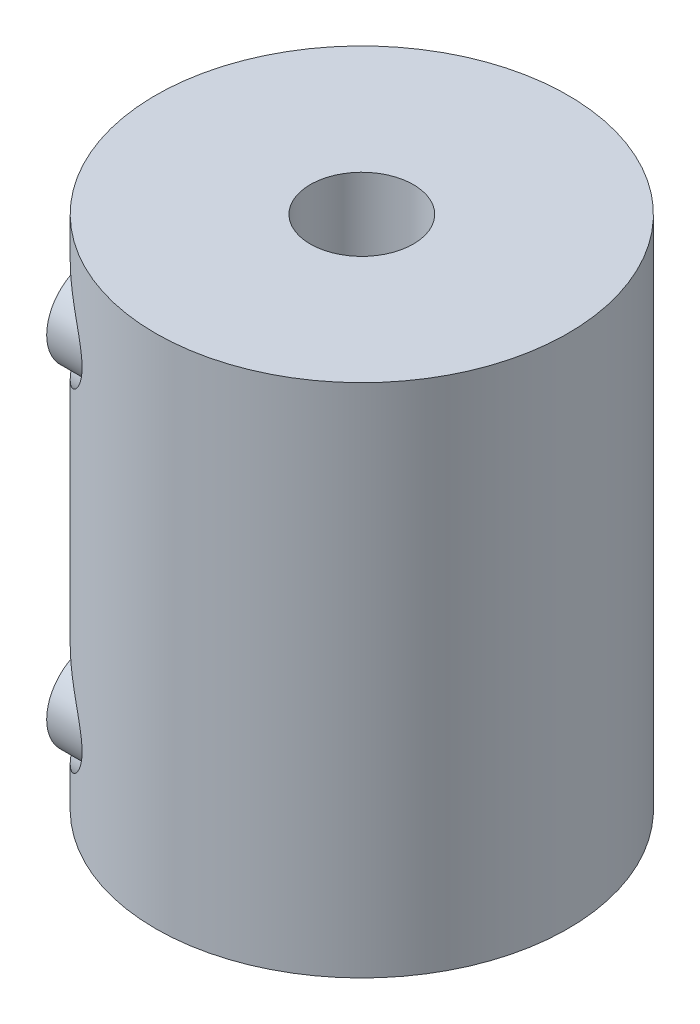
SolidWorks part; units mm, degrees
ref_plane "Front Plane" through (0, 0, 0) normal (0, 0, 1) x (1, 0, 0)
ref_plane "Top Plane" through (0, 0, 0) normal (0, 1, 0) x (1, 0, 0)
ref_plane "Right Plane" through (0, 0, 0) normal (1, 0, 0) x (0, 0, -1)
sketch "Sketch1" plane through (0, 0, 0) normal (0, 1, 0) x (1, 0, 0)
  circle A0 centre (0, 0) radius 10
  circle A1 centre (0, 0) radius 2.5
  dimension "D1" = 5
  dimension "D2" = 20
extrude "Boss-Extrude1" add sketch "Sketch1" along normal blind 25
sketch "Sketch2" plane through (0, 0, 0) normal (1, 0, 0) x (0, 0, -1)
  line L0 (-10, 12.5) -> (10, 12.5) construction
  line L1 (-10, 25) -> (-10, 0) construction
  line L2 (10, 0) -> (10, 25) construction
  circle A0 centre (-6.0788, 20.5708) radius 2.7027
  circle A1 centre (-6.0788, 4.4292) radius 2.7027
extrude "Cut-Extrude1" cut sketch "Sketch2" against normal through all from offset 4 offset against normal yes
sketch "Sketch3" plane through (-4, 0, 0) normal (-1, 0, 0) x (0, 0, 1)
  circle A3 centre (6.0788, 4.4292) radius 2.2027
  circle A4 centre (6.0788, 4.4292) radius 2.2027
  circle A6 centre (6.0788, 20.5708) radius 2.2027
  circle A7 centre (6.0788, 20.5708) radius 2.2027
  dimension "D1" = 0.5
  dimension "D2" = 0.5
extrude "Boss-Extrude2" add sketch "Sketch3" along normal blind 3
